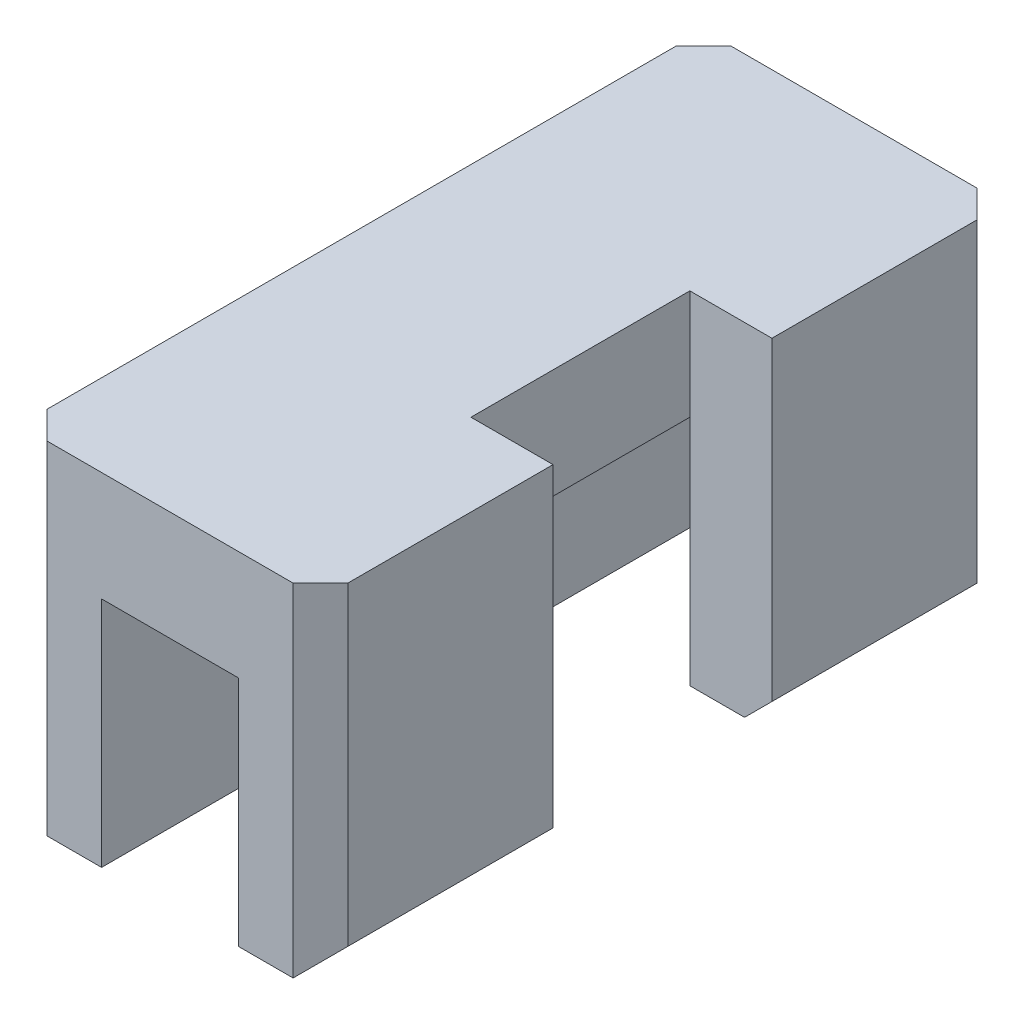
SolidWorks part; units mm, degrees
material "ABS"
ref_plane "Piano frontale" through (0, 0, 0) normal (0, 0, 1) x (1, 0, 0)
ref_plane "Piano superiore" through (0, 0, 0) normal (0, 1, 0) x (1, 0, 0)
ref_plane "Piano destro" through (0, 0, 0) normal (1, 0, 0) x (0, 0, -1)
sketch "Schizzo1" plane through (0, 0, 0) normal (0, 0, 1) x (1, 0, 0)
  line L7 (5, 0) -> (-5, 0)
  line L8 (-5, 0) -> (-5, -17)
  line L9 (-5, -17) -> (-11, -17)
  line L10 (-11, -17) -> (-11, 8)
  line L11 (-11, 8) -> (11, 8)
  line L12 (11, 8) -> (11, -17)
  line L13 (11, -17) -> (5, -17)
  line L14 (5, -17) -> (5, 0)
  dimension "D1" = 10
  dimension "D2" = 6
  dimension "D3" = 8
  dimension "D4" = 25
extrude "Estrusione-Estrusione1" add sketch "Schizzo1" along normal blind 50
sketch "Schizzo2" plane through (11, 0, 0) normal (1, 0, 0) x (0, 0, -1)
  line L0 (-50, -17) -> (0, -17) construction
  line L1 (-17, -17) -> (-33, -17)
  line L2 (-17, -17) -> (-17, 8)
  line L3 (-17, 8) -> (-33, 8)
  line L4 (-33, -17) -> (-33, 8)
  line L5 (-25, -17) -> (-25, 8) construction
  line L6 (-50, 8) -> (0, 8) construction
  point P10 (-28, 5)
  dimension "D1" = 16
extrude "Taglio-Estrusione1" cut sketch "Schizzo2" against normal blind 6
sketch "Schizzo3" plane through (-5, 0, 0) normal (1, 0, 0) x (0, 0, -1)
  circle A0 centre (-25, -5.5) radius 2.25
  dimension "D1" = 4.5
extrude "Taglio-Estrusione2" cut sketch "Schizzo3" against normal blind 10
chamfer "Smusso1" distance 2 angle 45 7 edges at (-11, -4.5, 50) (-11, -17, 25) (-11, -4.5, 0) (11, -4.5, 0) (11, -17, 8.5) (11, -17, 41.5) (11, -4.5, 50)
